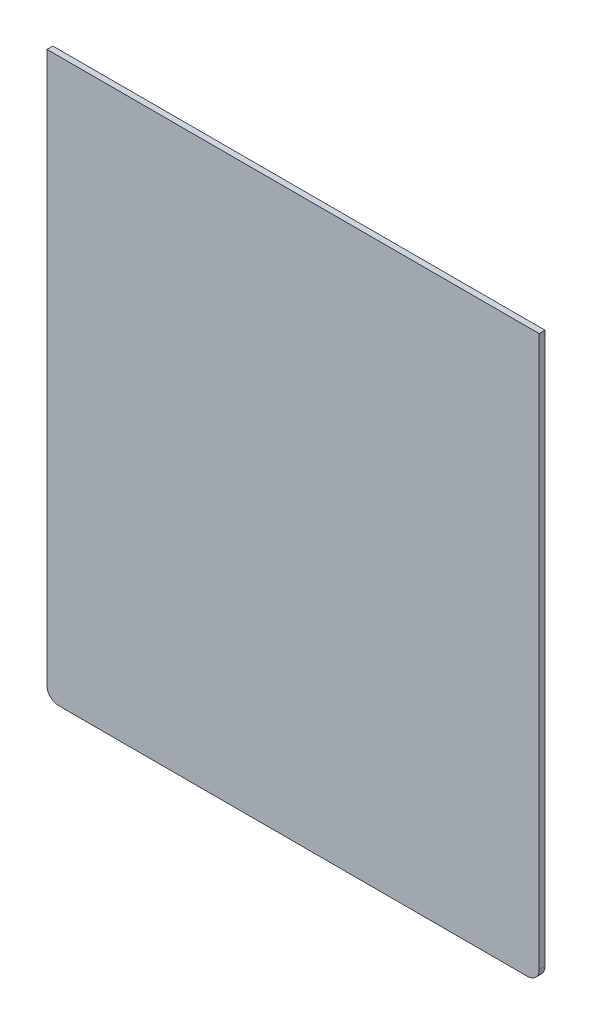
SolidWorks part; units mm, degrees
ref_plane "前视基准面" through (0, 0, 0) normal (0, 0, 1) x (1, 0, 0)
ref_plane "上视基准面" through (0, 0, 0) normal (0, 1, 0) x (1, 0, 0)
ref_plane "右视基准面" through (0, 0, 0) normal (1, 0, 0) x (0, 0, -1)
sketch "草图1" plane through (0, 0, 0) normal (0, 0, 1) x (1, 0, 0)
  line L1 (-210, -240) -> (210, -240)
  line L2 (-210, -240) -> (-210, 240)
  line L3 (-210, 240) -> (210, 240)
  line L4 (210, -240) -> (210, 240)
  line L5 (-210, -240) -> (210, 240) construction
  line L6 (-210, 240) -> (210, -240) construction
  point P0 (0, 0)
  dimension "D1" = 420
  dimension "D2" = 480
extrude "凸台-拉伸1" add sketch "草图1" along normal blind 5
fillet "圆角1" radius 10 2 edges at (-210, -240, 2.5) (210, -240, 2.5)
